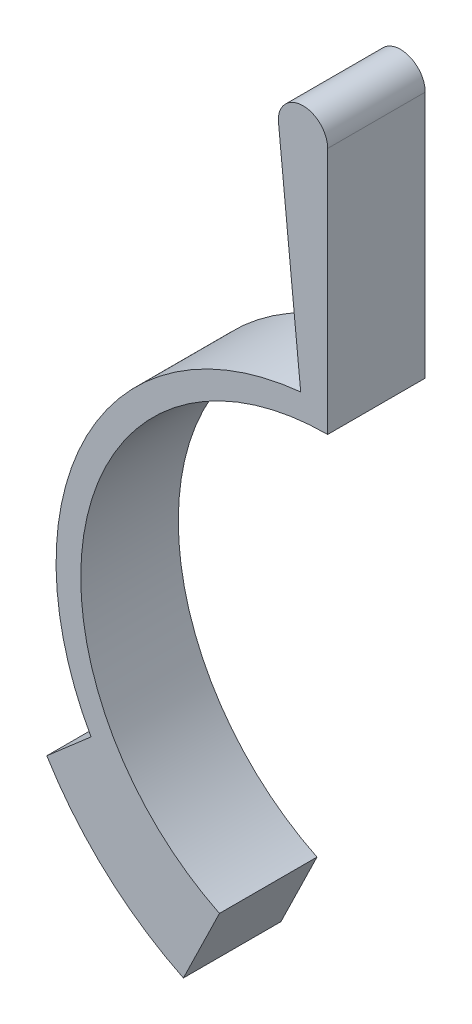
SolidWorks part; units mm, degrees
ref_plane "Plano frontal" through (0, 0, 0) normal (0, 0, 1) x (1, 0, 0)
ref_plane "Plano superior" through (0, 0, 0) normal (0, 1, 0) x (1, 0, 0)
ref_plane "Plano direito" through (0, 0, 0) normal (1, 0, 0) x (0, 0, -1)
sketch "Esboço1" plane through (0, 0, 0) normal (0, 0, 1) x (1, 0, 0)
  line L0 (2.4622, -10.7382) -> (2.4622, -0.6722)
  line L1 (-31.6634, -61.6056) -> (-26.2912, -56.9322)
  line L2 (-18.9512, -45.6683) -> (2.4622, -40.7382) construction
  line L3 (2.4622, -0.6722) -> (2.4622, 19.3608)
  line L4 (-0.8161, -7.9015) -> (-3.5378, 19.3608)
  line L6 (-15.0684, -76.6921) -> (-10.6857, -67.7036)
  arc A1 (2.4622, -10.7382) -> (-10.6857, -67.7036) centre (2.4622, -40.7382) ccw
  arc A2 (-0.8161, -7.9015) -> (-26.2912, -56.9322) centre (2.4622, -40.7382) ccw
  arc A3 (2.4622, 19.3608) -> (-3.4786, 18.7677) centre (-0.5378, 19.3608) ccw
  arc A5 (-31.6634, -61.6056) -> (-15.0684, -76.6921) centre (2.4622, -40.7382) ccw
  dimension "D1" = 6
  dimension "D2" = 30
  dimension "D3" = 33
  dimension "D4" = 40
extrude "Ressalto-extrusão1" add sketch "Esboço1" along normal up to vertex (106.1727 mm away)
ref_plane "Plano1" through (18.0373, -8.7947, 0) normal (0.8988, -0.4383, 0) x (0, 0, -1)
sketch "Esboço2" plane through (18.0373, -8.7947, 0) normal (0.8988, -0.4383, 0) x (0, 0, -1)
  line L0 (-11.85, -75.5383) -> (0, -75.5383)
  dimension "D1" = 11.85
  dimension "D2" = 11.85
scale "Escala1" scale about origin uniform scaling yes scale factor 0.681818
